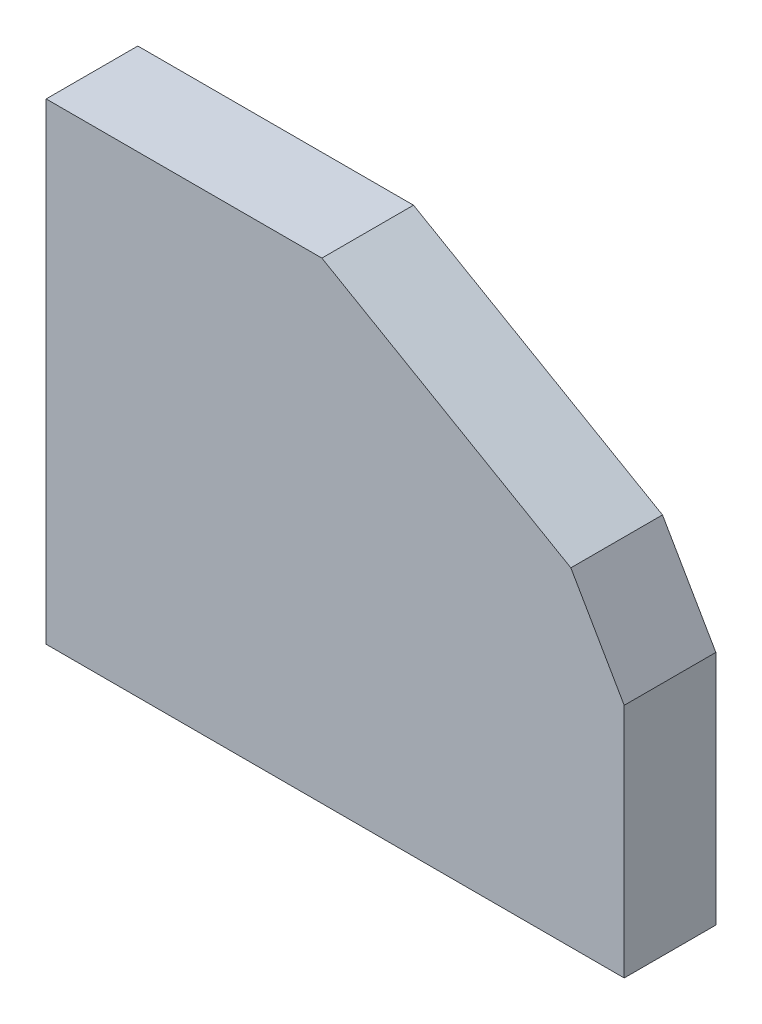
SolidWorks part; units mm, degrees
ref_plane "Alzado" through (0, 0, 0) normal (0, 0, 1) x (1, 0, 0)
ref_plane "Planta" through (0, 0, 0) normal (0, 1, 0) x (1, 0, 0)
ref_plane "Vista lateral" through (0, 0, 0) normal (1, 0, 0) x (0, 0, -1)
sketch "Croquis1" plane through (0, 0, 0) normal (0, 0, 1) x (1, 0, 0)
  line L1 (41, -33.5) -> (-41, -33.5)
  line L2 (41, -33.5) -> (41, 0)
  line L3 (-1.8874, 33.5) -> (-41, 33.5)
  line L4 (-41, -33.5) -> (-41, 33.5)
  line L5 (41, -33.5) -> (-41, 33.5) construction
  line L6 (23.2428, 18.9911) -> (-41, -33.5) construction
  line L8 (-41, 13.1084) -> (-41, -23.4216)
  line L9 (-41, -23.4216) -> (41, -23.4216)
  line L10 (41, 0) -> (41, -23.4216)
  line L14 (33.4319, 13.1084) -> (41, 0)
  line L16 (-1.8874, 33.5) -> (33.4319, 13.1084)
  point P0 (0, 0)
  dimension "D7" = 30
  dimension "D2" = 82
  dimension "D3" = 36.53
  dimension "D8" = 30
extrude "Saliente-Extruir1" add sketch "Croquis1" along normal blind 13 contours L14 L16 L3 L4 L1 L2
sketch "Croquis2" plane through (30.75, 17.7535, 0) normal (0.866, 0.5, 0) x (0, 0, -1)
  line L0 (-6.5, -20.5) -> (-6.5, -12.4538)
  line L1 (-13, -20.5) -> (0, -20.5) construction
  line L2 (-6.5, -12.4538) -> (-13, -12.4538)
  line L4 (-13, -5.3637) -> (-13, -20.5) construction
